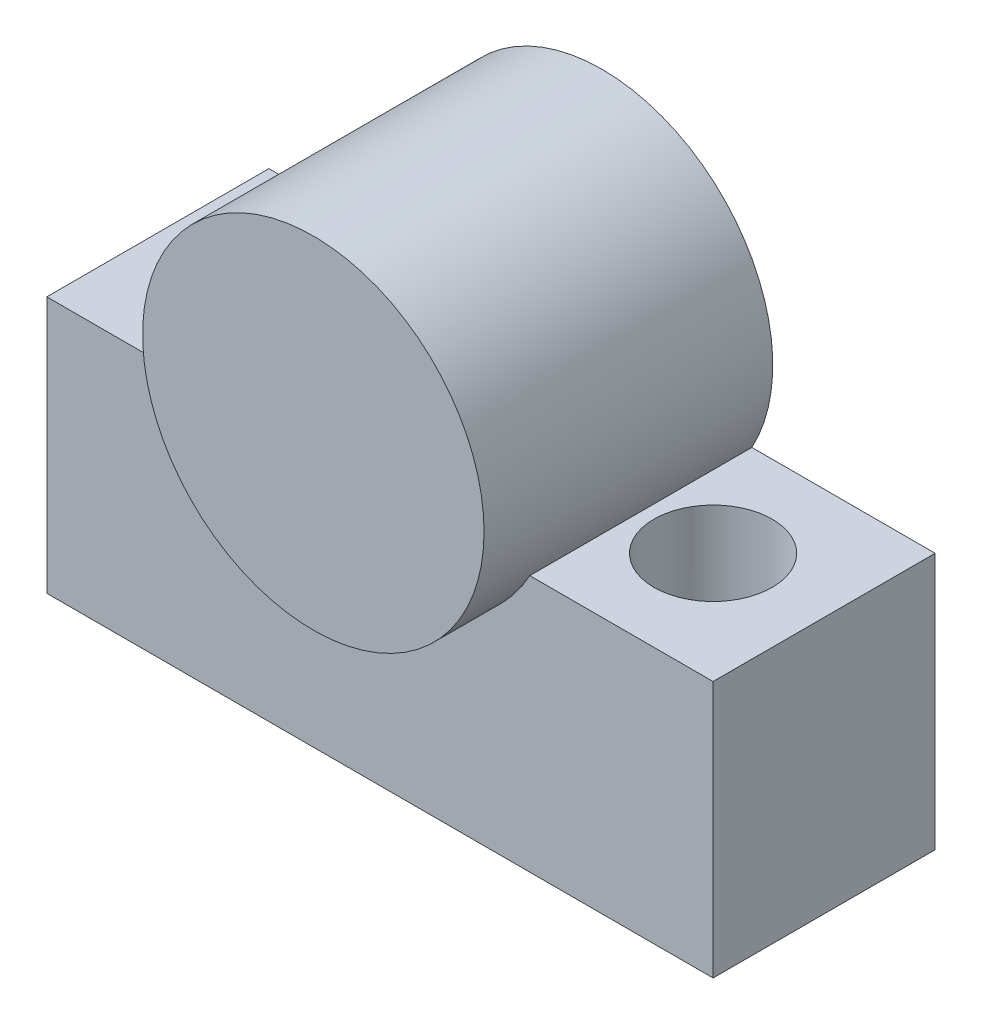
SolidWorks part; units mm, degrees
ref_plane "Front Plane" through (0, 0, 0) normal (0, 0, 1) x (1, 0, 0)
ref_plane "Top Plane" through (0, 0, 0) normal (0, 1, 0) x (1, 0, 0)
ref_plane "Right Plane" through (0, 0, 0) normal (1, 0, 0) x (0, 0, -1)
sketch "Sketch1" plane through (0, 0, 0) normal (0, 0, 1) x (1, 0, 0)
  line L0 (0, -3.9052) -> (-7.62, -3.9052)
  line L1 (-7.62, -3.9052) -> (-7.62, -1.8732)
  line L2 (-7.62, -1.8732) -> (-3.4266, -1.8732)
  line L3 (0, -3.9052) -> (7.62, -3.9052)
  line L4 (7.62, -3.9052) -> (7.62, -1.8732)
  line L5 (7.62, -1.8732) -> (3.4266, -1.8733)
  circle A0 centre (0, 0) radius 2.3813
  arc A1 (3.4266, -1.8733) -> (-3.4266, -1.8732) centre (0, 0) ccw
  dimension "D1" = 4.7625
  dimension "D2" = 1.524
  dimension "D3" = 2.032
  dimension "D4" = 2.032
  dimension "D5" = 7.62
  dimension "D6" = 7.62
extrude "Boss-Extrude1" add sketch "Sketch1" along normal blind 5.08
sketch "Sketch2" plane through (0, 0, 5.08) normal (0, 0, 1) x (1, 0, 0)
  circle A0 centre (0, 0) radius 3.9053
extrude "Boss-Extrude2" add sketch "Sketch2" along normal blind 1.524
hole_wizard "Tap Drill for #6-32 Tap1" positions "Sketch3" profile "Sketch4" hole size "#6-32" standard "ANSI Inch"
sketch "Sketch3" plane through (0, -1.8732, 0) normal (0, 1, 0) x (1, 0, 0)
  line L0 (-3.4266, 0) -> (-7.62, 0) construction
  line L1 (7.62, 0) -> (3.4266, 0) construction
  line L2 (-7.62, -5.08) -> (-7.62, 0) construction
  line L3 (7.62, -5.08) -> (7.62, 0) construction
  point P0 (-5.08, -2.54)
  point P2 (5.08, -2.54)
  dimension "D1" = 2.54
  dimension "D2" = 2.54
  dimension "D3" = 2.54
  dimension "D4" = 2.54
sketch "Sketch4" plane through (-5.08, -1.8732, 2.54) normal (1, 0, 0) x (0, 0, 1)
  line L0 (0, 0) -> (0, 8.4327)
  line L1 (0, 8.4327) -> (1.3525, 7.62)
  line L2 (1.3525, 7.62) -> (1.3525, 0)
  line L5 (1.3525, 0) -> (0, 0)
  line L10 (0, 8.4327) -> (-1.3526, 7.62) construction
  line L11 (0, -6.35) -> (0, 107.95) construction
  dimension "Hole Dia." = 2.7051
  dimension "Hole Depth" = 7.62
  dimension "Drill Angle" = 118
sketch "Sketch6" plane through (0, -3.9052, 0) normal (0, -1, 0) x (1, 0, 0)
  line L1 (-7.62, 0) -> (7.62, 0)
  line L2 (-7.62, 0) -> (-7.62, 5.08)
  line L3 (-7.62, 5.08) -> (7.62, 5.08)
  line L4 (7.62, 0) -> (7.62, 5.08)
  circle A0 centre (-5.08, 2.54) radius 1.3525
  circle A1 centre (5.08, 2.54) radius 1.3525
extrude "Boss-Extrude3" add sketch "Sketch6" along normal blind 3.8417
